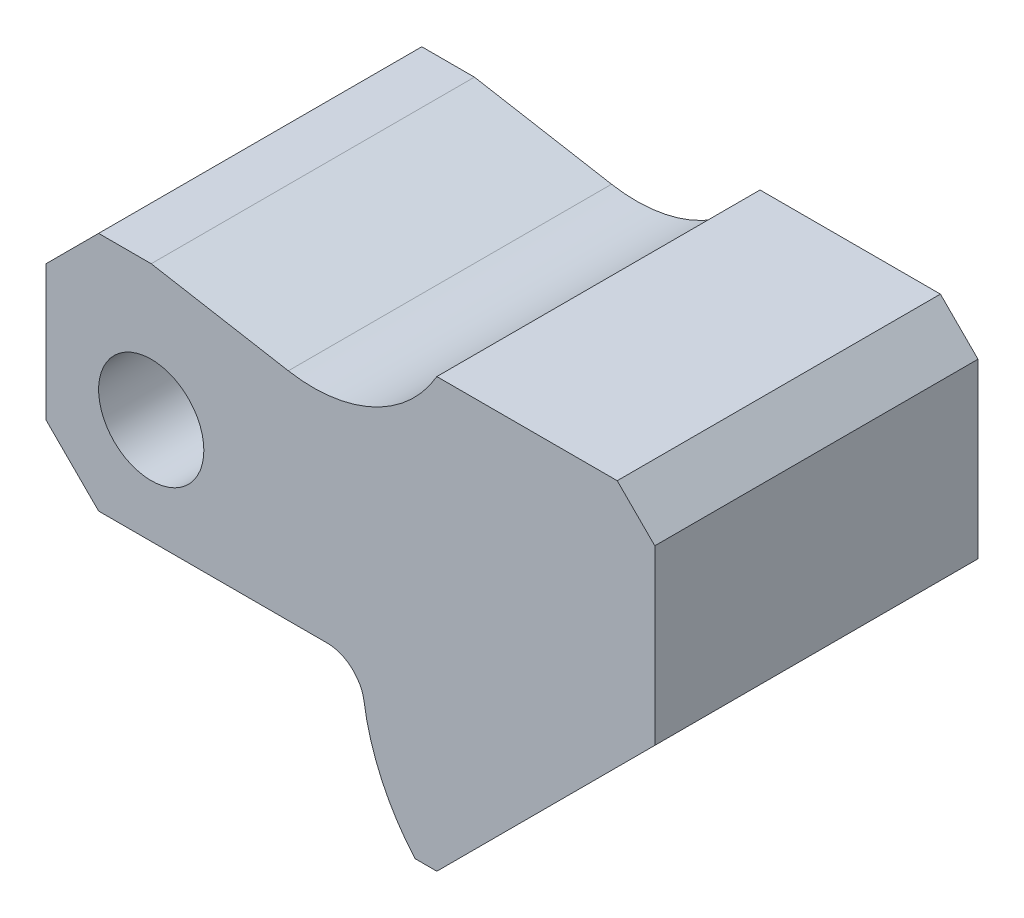
SolidWorks part; units mm, degrees
material "AISI 1020"
ref_plane "Front Plane" through (0, 0, 0) normal (0, 0, 1) x (1, 0, 0)
ref_plane "Top Plane" through (0, 0, 0) normal (0, 1, 0) x (1, 0, 0)
ref_plane "Right Plane" through (0, 0, 0) normal (1, 0, 0) x (0, 0, -1)
other "ANSI"
other "ANSI 1020 Steel"
sketch "Sketch1" plane through (0, 0, 0) normal (0, 0, 1) x (1, 0, 0)
  line L0 (0, 0) -> (7, 7)
  line L1 (7, 7) -> (14, 7)
  line L2 (14, 7) -> (32.2431, 3.7833)
  line L3 (52, 13) -> (76, 13)
  line L4 (76, 13) -> (81, 8)
  line L5 (81, 8) -> (81, -15)
  line L6 (81, -15) -> (52, -44)
  line L7 (52, -44) -> (49.0911, -44)
  line L8 (0, 0) -> (0, -18)
  line L9 (0, -18) -> (7, -25)
  line L10 (7, -25) -> (37.3697, -25)
  arc A0 (32.2431, 3.7833) -> (52, 13) centre (35.5424, 22.4946) ccw
  arc A1 (37.3697, -25) -> (42.3153, -29.2647) centre (37.3697, -30) cw
  arc A2 (42.3153, -29.2647) -> (49.0911, -44) centre (71, -25) ccw
  circle A3 centre (14, -11) radius 7
  point P17 (0, 0)
  point P19 (0, 0)
  point P20 (0, -12.189)
  dimension "D11" = 19
  dimension "D12" = 5
  dimension "D13" = 29
  dimension "D18" = 14
  dimension "D1" = 81
  dimension "D2" = 57
  dimension "D3" = 7
  dimension "D4" = 14
  dimension "D5" = 32
  dimension "D6" = 7
  dimension "D7" = 45
  dimension "D8" = 19
  dimension "D9" = 10
  dimension "D10" = 45
  dimension "D14" = 19
  dimension "D15" = 29
  dimension "D16" = 29
  dimension "D17" = 5
  dimension "D19" = 14
  dimension "D20" = 14
extrude "Boss-Extrude2" add sketch "Sketch1" along normal blind 43
equation "\"A\"= 81"
equation "\"B\"= 57"
equation "\"C\"= 43"
equation "\"D1@Sketch1\"=\"A\""
equation "\"D2@Sketch1\"=\"B\""
equation "\"D1@Boss-Extrude2\"=\"C\""
